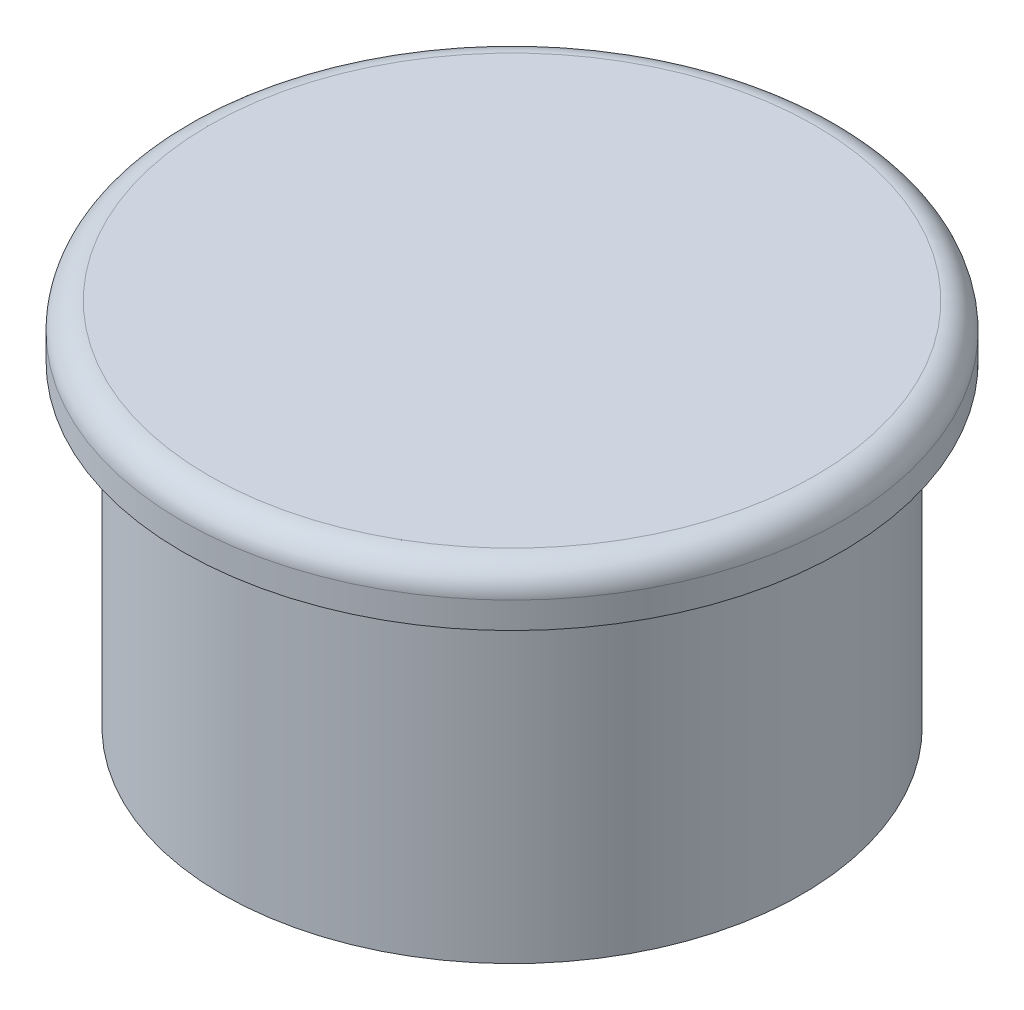
SolidWorks part; units mm, degrees
material "Silicon Rubber"
ref_plane "Front Plane" through (0, 0, 0) normal (0, 0, 1) x (1, 0, 0)
ref_plane "Top Plane" through (0, 0, 0) normal (0, 1, 0) x (1, 0, 0)
ref_plane "Right Plane" through (0, 0, 0) normal (1, 0, 0) x (0, 0, -1)
sketch "Sketch2" plane through (0, 0, 0) normal (0, 1, 0) x (1, 0, 0)
  circle A0 centre (0, 0) radius 11
  circle A1 centre (0, 0) radius 9
  dimension "D1" = 22
  dimension "D2" = 18
extrude "Boss-Extrude1" add sketch "Sketch2" along normal blind 12
sketch "Sketch3" plane through (0, 12, 0) normal (0, 1, 0) x (1, 0, 0)
  circle A0 centre (0, 0) radius 12.5
  dimension "D1" = 25
extrude "Boss-Extrude2" add sketch "Sketch3" along normal blind 2
fillet "Fillet1" radius 1 1 edges at (0, 14, 12.5)
